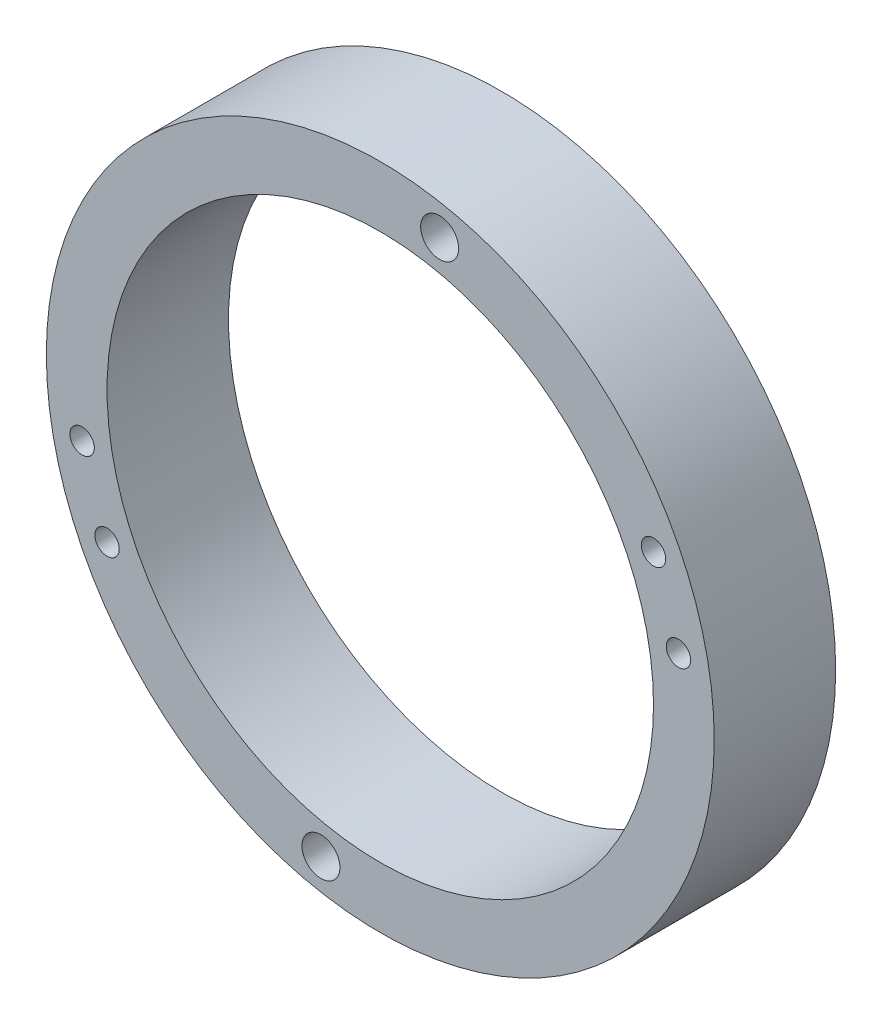
SolidWorks part; units mm, degrees
ref_plane "Front Plane" through (0, 0, 0) normal (0, 0, 1) x (1, 0, 0)
ref_plane "Top Plane" through (0, 0, 0) normal (0, 1, 0) x (1, 0, 0)
ref_plane "Right Plane" through (0, 0, 0) normal (1, 0, 0) x (0, 0, -1)
sketch "Sketch1" plane through (0, 0, 0) normal (0, 0, 1) x (1, 0, 0)
  line L0 (69.85, 0) -> (57.15, 0) construction
  line L1 (-69.85, 0) -> (69.85, 0) construction
  dimension "OD" = 139.7
  dimension "Wall Thickness" = 12.7
sketch "Sketch2" plane through (0, 0, 0) normal (1, 0, 0) x (0, 0, -1)
  line L0 (12.7, 0) -> (-12.7, 0)
  point P4 (0, 0)
  dimension "Length" = 25.4
sketch "Sketch3" plane through (0, 0, 0) normal (0, 0, 1) x (1, 0, 0)
  circle A0 centre (0, 0) radius 69.85
  circle A1 centre (0, 0) radius 57.15
extrude "Boss-Extrude1" add sketch "Sketch3" along normal up to vertex (12.7 mm away) and the other way up to vertex (12.7 mm away) up to point (0, 0, 12.7) other way up to point (0, 0, -12.7)
sketch "Sketch4" plane through (0, 0, 12.7) normal (0, 0, 1) x (1, 0, 0)
  line L0 (0, 0) -> (-51.435, -24.9111) construction
  line L1 (-44.45, -96.1119) -> (44.45, -96.1119) construction
  line L2 (-44.45, -96.1119) -> (-44.45, 96.1119) construction
  line L3 (-44.45, 96.1119) -> (44.45, 96.1119) construction
  line L4 (44.45, -96.1119) -> (44.45, 96.1119) construction
  line L5 (-44.45, -96.1119) -> (44.45, 96.1119) construction
  line L6 (-44.45, 96.1119) -> (44.45, -96.1119) construction
  line L7 (-51.435, -24.9111) -> (-62.865, -30.4469) construction
  line L8 (0, 0) -> (-56.1299, -10.7499) construction
  line L9 (-56.1299, -10.7499) -> (-68.6032, -13.1388) construction
  line L10 (0, 0) -> (-11.1721, -56.0474) construction
  line L11 (-11.1721, -56.0474) -> (-13.6548, -68.5023) construction
  circle A0 centre (0, 0) radius 57.15 construction
  circle A1 centre (0, 0) radius 69.85 construction
  arc A2 (-56.1299, -10.7499) -> (-50.0123, 27.6566) centre (0, 0) cw construction
  arc A3 (-50.0123, 27.6566) -> (-44.45, 35.921) centre (0, 0) cw construction
  arc A4 (-44.45, -35.921) -> (-11.1721, -56.0474) centre (0, 0) ccw construction
  point P0 (0, 0)
  point P10 (-62.3665, -11.9444)
  point P16 (-57.15, -27.679)
  point P18 (-44.45, -35.921)
  point P22 (-44.45, 35.921)
  point P42 (-12.4134, -62.2748)
  dimension "D5" = 10
  dimension "D1" = 88.9
  dimension "D2" = 192.2238
  dimension "D3" = 12.7
  dimension "D4" = 15
hole_wizard "Tap Drill for 1/4-20 Tap1" positions "Sketch4" profile "Sketch5" hole size "1/4-20" standard "ANSI Inch"
sketch "Sketch5" plane through (-57.15, -27.679, 12.7) normal (1, 0, 0) x (0, -1, 0)
  line L0 (0, 0) -> (0, 25.4)
  line L1 (0, 25.4) -> (2.5527, 25.4)
  line L2 (2.5527, 25.4) -> (2.5527, 0)
  line L5 (2.5527, 0) -> (0, 0)
  line L11 (0, -6.35) -> (0, 107.95) construction
  dimension "Thru Hole Dia." = 5.1054
  dimension "Thru Hole Depth" = 25.4
sketch "Sketch6" plane through (0, 0, 12.7) normal (0, 0, 1) x (1, 0, 0)
  point P0 (-12.4134, -62.2748)
hole_wizard "5/16 (0.3125) Diameter Hole1" positions "Sketch6" profile "Sketch7" hole size "5/16" standard "ANSI Inch" end condition through all
sketch "Sketch7" plane through (-12.4134, -62.2748, 12.7) normal (1, 0, 0) x (0, -1, 0)
  line L0 (0, 0) -> (0, 25.4)
  line L1 (0, 25.4) -> (3.9687, 25.4)
  line L2 (3.9687, 25.4) -> (3.9687, 0)
  line L5 (3.9687, 0) -> (0, 0)
  line L11 (0, -6.35) -> (0, 107.95) construction
  dimension "Thru Hole Dia." = 7.9375
  dimension "Thru Hole Depth" = 25.4
pattern_circular "CirPattern1" count 2 over 360 about axis through (0, 0, 0) along (0, 0, 1) of "Tap Drill for 1/4-20 Tap1", "5/16 (0.3125) Diameter Hole1"
